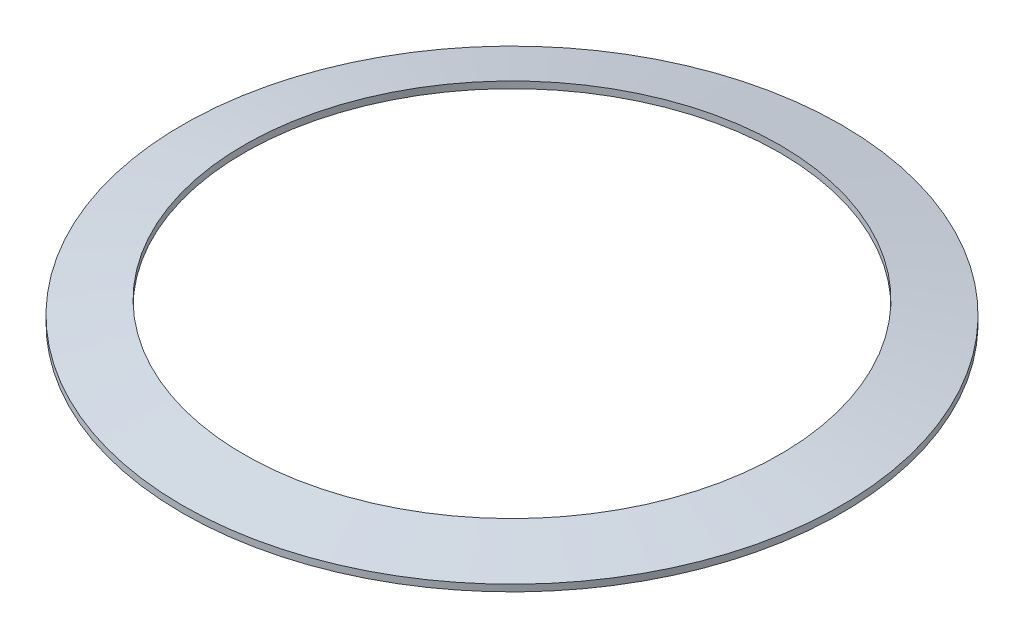
SolidWorks part; units mm, degrees
ref_plane "Plano frontal" through (0, 0, 0) normal (0, 0, 1) x (1, 0, 0)
ref_plane "Plano superior" through (0, 0, 0) normal (0, 1, 0) x (1, 0, 0)
ref_plane "Plano direito" through (0, 0, 0) normal (1, 0, 0) x (0, 0, -1)
sketch "Esboço1" plane through (0, 0, 0) normal (0, 0, 1) x (1, 0, 0)
  line L0 (0, -4.8222) -> (0, 5.6222) construction
  line L1 (49.5, 0) -> (49.5, 1)
  line L2 (49.5, 1) -> (40.25, 3)
  line L3 (40.25, 3) -> (40.25, 2)
  line L4 (40.25, 2) -> (49.5, 0)
  dimension "D1" = 1
  dimension "D2" = 1
  dimension "D3" = 40.25
  dimension "D4" = 49.5
  dimension "D5" = 2
revolve "Revolução1" add sketch "Esboço1" angle 360 about L0
